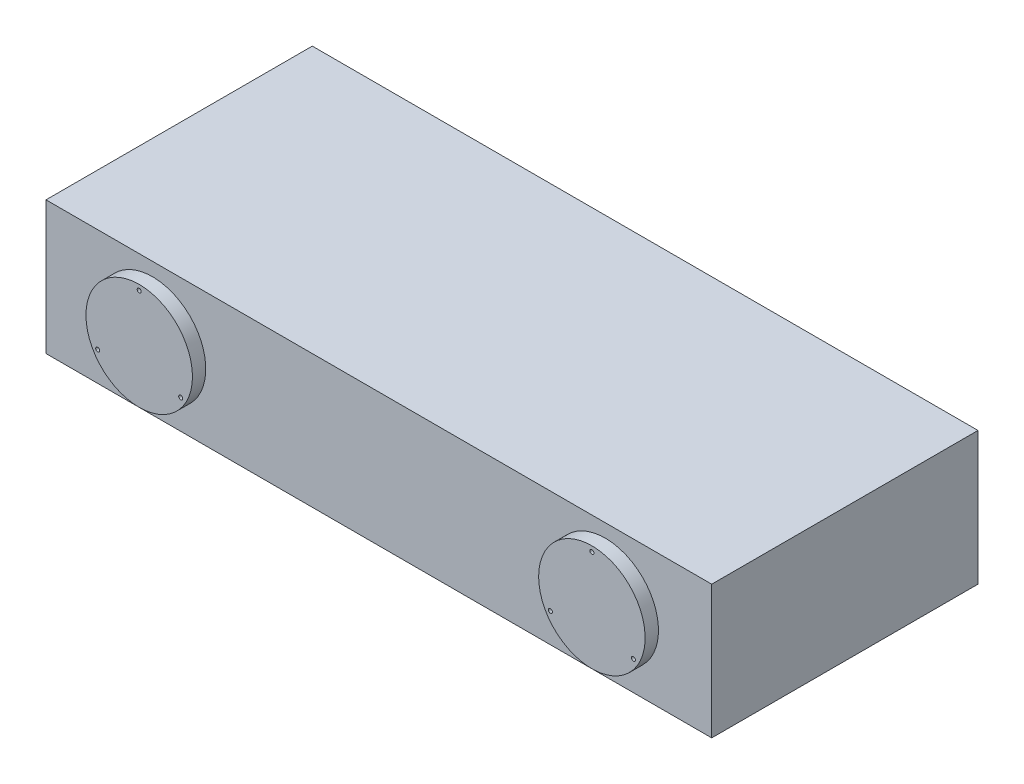
SolidWorks part; units mm, degrees
ref_plane "Front Plane" through (0, 0, 0) normal (0, 0, 1) x (1, 0, 0)
ref_plane "Top Plane" through (0, 0, 0) normal (0, 1, 0) x (1, 0, 0)
ref_plane "Right Plane" through (0, 0, 0) normal (1, 0, 0) x (0, 0, -1)
sketch "Sketch1" plane through (0, 0, 0) normal (0, 1, 0) x (1, 0, 0)
  line L1 (250, -100) -> (-250, -100)
  line L2 (250, -100) -> (250, 100)
  line L3 (250, 100) -> (-250, 100)
  line L4 (-250, -100) -> (-250, 100)
  line L5 (250, -100) -> (-250, 100) construction
  line L6 (250, 100) -> (-250, -100) construction
  point P0 (0, 0)
  dimension "D1" = 500
  dimension "D2" = 200
extrude "Boss-Extrude1" add sketch "Sketch1" along normal blind 100
sketch "Sketch2" plane through (0, 0, 100) normal (0, 0, 1) x (1, 0, 0)
  line L0 (-1250, 50) -> (48750, 50) construction
  line L1 (-250, 100) -> (-250, 0) construction
  circle A1 centre (-170, 50) radius 40
  point P5 (0, 0)
  point P9 (-250, 50)
  point P10 (0, 0)
  point P11 (0, 0)
  dimension "D1" = 80
  dimension "D2" = 80
extrude "Boss-Extrude2" add sketch "Sketch2" along normal blind 10
sketch "Sketch5" plane through (0, 0, 110) normal (0, 0, 1) x (1, 0, 0)
  line L0 (-170, -897.1498) -> (-170, 49102.8502) construction
  circle A0 centre (-170, 86) radius 1.5
  circle A3 centre (-170, 50) radius 40 construction
  point P5 (-170, 90)
  point P8 (-170, 50)
  dimension "D1" = 3
  dimension "D2" = 4
extrude "Cut-Extrude3" cut sketch "Sketch5" against normal blind 20
pattern_circular "CirPattern2" count 3 over 360 about axis through (-170, 50, 0) along (0, 0, 1) of "Cut-Extrude3"
mirror "Mirror4" about plane through (0, 0, 0) normal (1, 0, 0) of "CirPattern2", "Boss-Extrude2", "Cut-Extrude3"
mirror "Mirror5" about plane through (0, 0, 0) normal (0, 0, 1) of "Mirror4", "CirPattern2", "Cut-Extrude3", "Boss-Extrude2"
